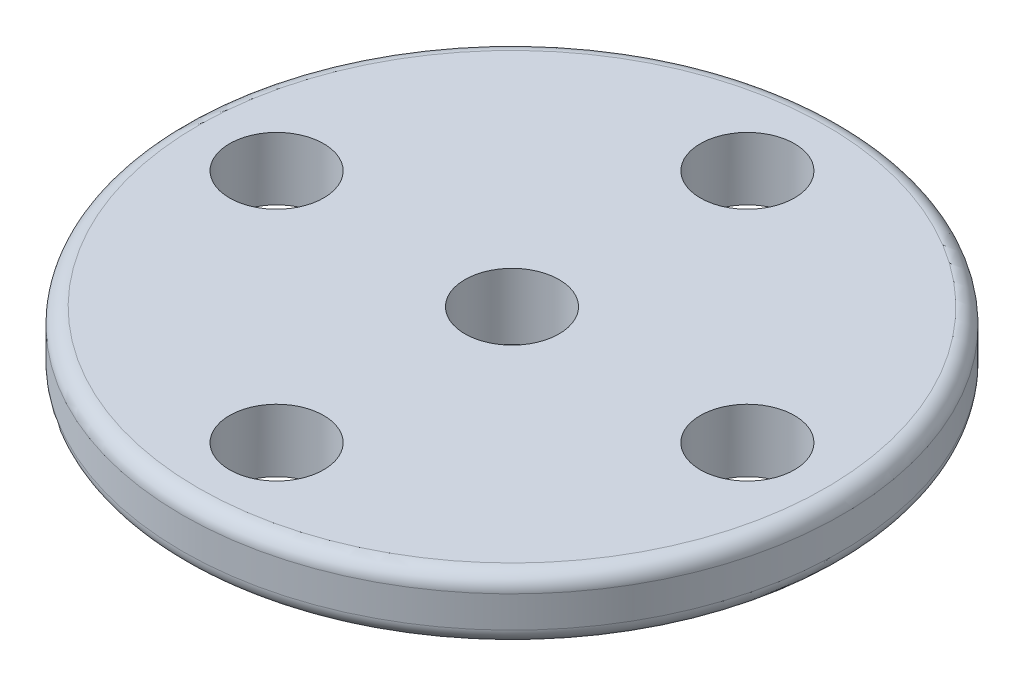
SolidWorks part; units mm, degrees
material "ABS"
ref_plane "Front Plane" through (0, 0, 0) normal (0, 0, 1) x (1, 0, 0)
ref_plane "Top Plane" through (0, 0, 0) normal (0, 1, 0) x (1, 0, 0)
ref_plane "Right Plane" through (0, 0, 0) normal (1, 0, 0) x (0, 0, -1)
sketch "Sketch1" plane through (0, 0, 0) normal (0, 0, 1) x (1, 0, 0)
  line L0 (3, 0) -> (3, 3.4)
  line L1 (4.5, 0) -> (4.5, 3.5)
  line L2 (4.5, 3.5) -> (10.5, 3.5)
  line L3 (10.5, 3.5) -> (10.5, 5.5)
  line L4 (10.5, 5.5) -> (1.5, 5.5)
  line L5 (0, 0) -> (0, 5.5) construction
  line L6 (3, 0) -> (4.5, 0)
  line L7 (3, 3.4) -> (1.5, 3.4)
  line L8 (1.5, 3.4) -> (1.5, 5.5)
  dimension "D1" = 5.5
  dimension "D2" = 2
  dimension "D3" = 10.5
  dimension "D4" = 4.5
  dimension "D5" = 3
  dimension "D6" = 3.4
  dimension "D7" = 1.5
revolve "Revolve1" add sketch "Sketch1" angle 360 about L5
fillet "Fillet1" radius 0.5 3 edges at (0, 3.5, -4.5) (0, 5.5, -10.5) (0, 3.5, -10.5)
sketch "Sketch2" plane through (0, 5.5, 0) normal (0, 1, 0) x (1, 0, 0)
  circle A0 centre (0, 0) radius 7.5 construction
  circle A1 centre (0, 7.5) radius 1.5
  circle A2 centre (-7.5, 0) radius 1.5
  circle A3 centre (0, -7.5) radius 1.5
  circle A4 centre (7.5, 0) radius 1.5
  dimension "D1" = 15
  dimension "D2" = 3
extrude "Cut-Extrude1" cut sketch "Sketch2" against normal through all
